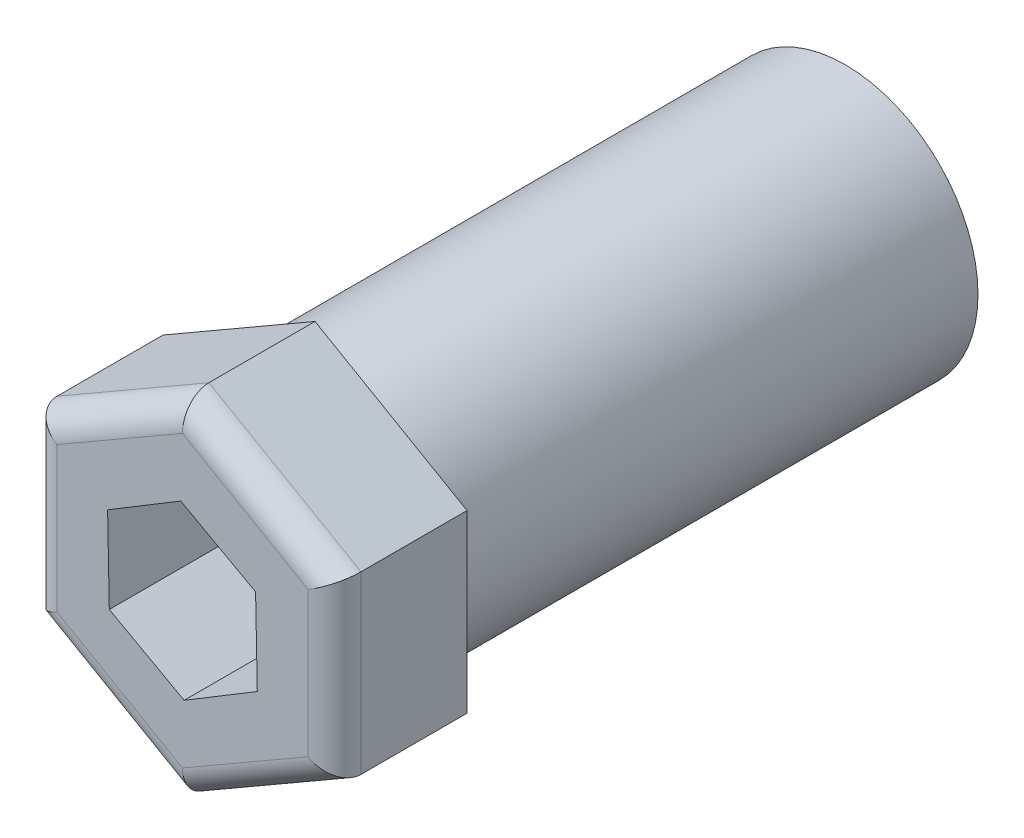
SolidWorks part; units mm, degrees
ref_plane "Front Plane" through (0, 0, 0) normal (0, 0, 1) x (1, 0, 0)
ref_plane "Top Plane" through (0, 0, 0) normal (0, 1, 0) x (1, 0, 0)
ref_plane "Right Plane" through (0, 0, 0) normal (1, 0, 0) x (0, 0, -1)
sketch "Sketch1" plane through (0, 0, 0) normal (0, 0, 1) x (1, 0, 0)
  circle A0 centre (0, 0) radius 1
  dimension "D1" = 2
extrude "Boss-Extrude1" add sketch "Sketch1" along normal blind 4
sketch "Sketch2" plane through (0, 0, 4) normal (0, 0, 1) x (1, 0, 0)
  line L1 (0, 1.3237) -> (-1.1464, 0.6619)
  line L2 (-1.1464, 0.6619) -> (-1.1464, -0.6619)
  line L3 (-1.1464, -0.6619) -> (0, -1.3237)
  line L4 (0, -1.3237) -> (1.1464, -0.6619)
  line L5 (1.1464, -0.6619) -> (1.1464, 0.6619)
  line L6 (1.1464, 0.6619) -> (0, 1.3237)
  circle A0 centre (0, 0) radius 1.1464 construction
extrude "Boss-Extrude2" add sketch "Sketch2" along normal blind 1
sketch "Sketch3" plane through (0, 0, 5) normal (0, 0, 1) x (1, 0, 0)
  line L1 (-0.5645, 0.3111) -> (-0.5517, -0.3333)
  line L2 (-0.5517, -0.3333) -> (0.0128, -0.6444)
  line L3 (0.0128, -0.6444) -> (0.5645, -0.3111)
  line L4 (0.5645, -0.3111) -> (0.5517, 0.3333)
  line L5 (0.5517, 0.3333) -> (-0.0128, 0.6444)
  line L6 (-0.0128, 0.6444) -> (-0.5645, 0.3111)
  circle A0 centre (0, 0) radius 0.5582 construction
  point P1 (0.5517, -0.3333)
extrude "Cut-Extrude1" cut sketch "Sketch3" against normal blind 1
fillet "Fillet1" radius 0.2 6 edges at (0.5732, -0.9928, 5) (-0.5732, -0.9928, 5) (-1.1464, 0, 5) (-0.5732, 0.9928, 5) (0.5732, 0.9928, 5) (1.1464, 0, 5)
